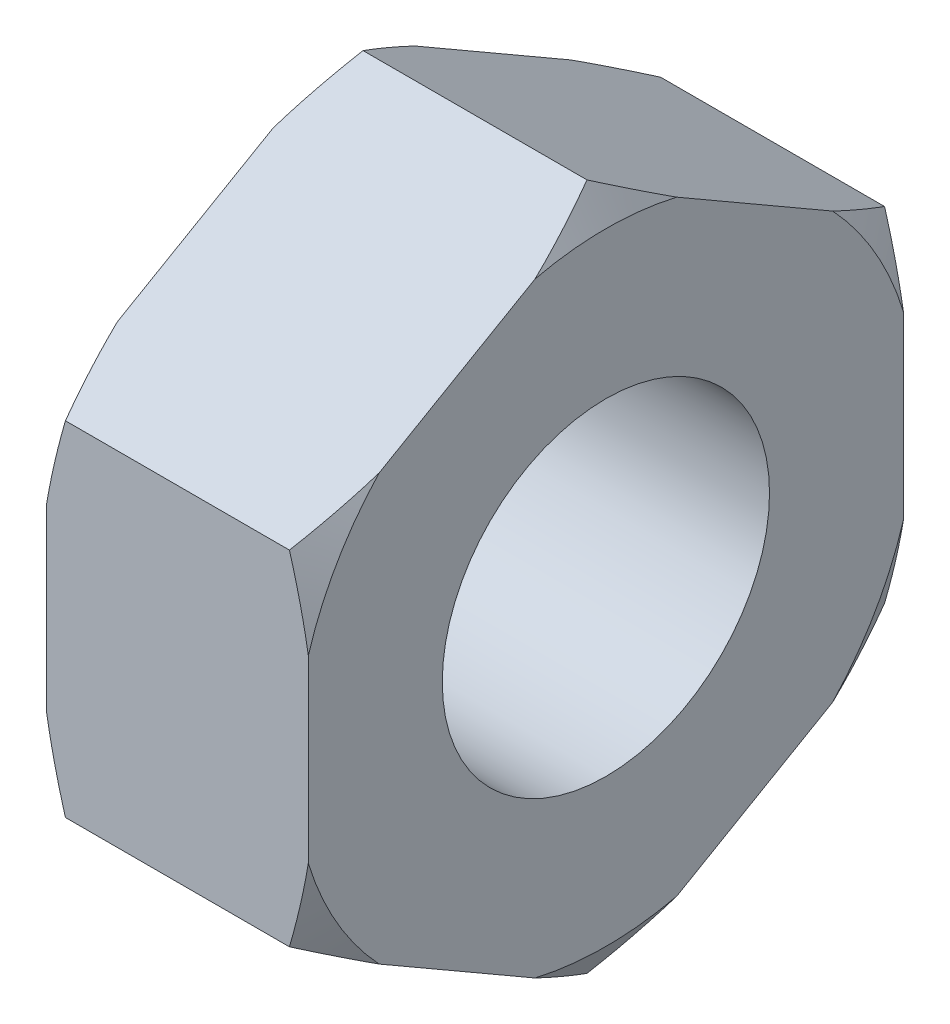
SolidWorks part; units mm, degrees
ref_plane "Спереди" through (0, 0, 0) normal (0, 0, 1) x (1, 0, 0)
ref_plane "Сверху" through (0, 0, 0) normal (0, 1, 0) x (1, 0, 0)
ref_plane "Справа" through (0, 0, 0) normal (1, 0, 0) x (0, 0, -1)
sketch "Эскиз1" plane through (0, 0, 0) normal (0, 0, 1) x (1, 0, 0)
  line L0 (-3.8763, 0) -> (5.024, 0) construction
  line L1 (-0.4961, 1) -> (1.1039, 1)
  line L2 (1.1039, 1) -> (1.1039, 1.9)
  line L3 (0.9884, 2.1) -> (-0.3806, 2.1)
  line L4 (-0.4961, 1.9) -> (-0.4961, 1)
  line L5 (-0.3806, 2.1) -> (-0.4961, 1.9)
  line L6 (1.1039, 1.9) -> (0.9884, 2.1)
  dimension "D1" = 2
  dimension "D2" = 30
  dimension "D3" = 0.2
  dimension "D4" = 30
  dimension "D5" = 0.2
  dimension "D6" = 4.2
  dimension "D7" = 1.6
revolve "Повернуть1" add sketch "Эскиз1" angle 360 about L0
sketch "Эскиз3" plane through (-0.4961, 0, 0) normal (-1, 0, 0) x (0, 0, 1)
  line L0 (0, 2.1) -> (0, -2.1) construction
  line L1 (-2.1, 0) -> (2.1, 0) construction
  line L3 (0, 2.1) -> (-1.8187, 1.05)
  line L4 (-1.8187, 1.05) -> (-1.8187, -1.05)
  line L5 (-1.8187, -1.05) -> (0, -2.1)
  line L6 (0, -2.1) -> (1.8187, -1.05)
  line L7 (1.8187, -1.05) -> (1.8187, 1.05)
  line L8 (1.8187, 1.05) -> (0, 2.1)
  circle A0 centre (0, 0) radius 2.1 construction
  circle A1 centre (0, 0) radius 1.8187 construction
extrude "Вырез-Вытянуть4" cut sketch "Эскиз3" against normal blind 10 flip side to cut
